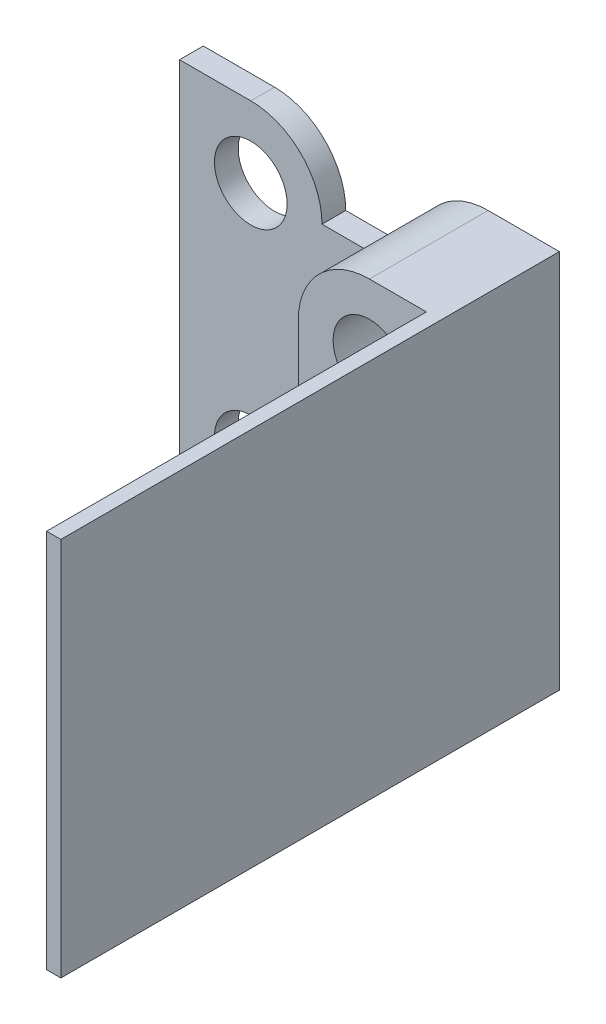
SolidWorks part; units mm, degrees
ref_plane "Front Plane" through (0, 0, 0) normal (0, 0, 1) x (1, 0, 0)
ref_plane "Top Plane" through (0, 0, 0) normal (0, 1, 0) x (1, 0, 0)
ref_plane "Right Plane" through (0, 0, 0) normal (1, 0, 0) x (0, 0, -1)
sketch "Sketch1" plane through (0, 0, 0) normal (0, 0, 1) x (1, 0, 0)
  line L0 (45, 50) -> (0, 50) construction
  line L1 (0, 50) -> (0, 0) construction
  line L2 (-15, 65) -> (0, 65)
  line L3 (60, 65) -> (60, 41.9663)
  line L4 (15, 50) -> (30, 50)
  line L5 (12.6521, -15) -> (-15, -15)
  line L6 (-15, -15) -> (-15, 65)
  line L7 (60, 41.9663) -> (60, -15)
  line L8 (60, -15) -> (12.6521, -15)
  line L9 (45, 65) -> (60, 65)
  circle A0 centre (0, 0) radius 7.65
  circle A1 centre (45, 50) radius 7.65
  circle A2 centre (0, 50) radius 7.65
  arc A3 (45, 65) -> (30, 50) centre (45, 50) ccw
  arc A4 (0, 65) -> (15, 50) centre (0, 50) cw
  dimension "D1" = 15.3
  dimension "D4" = 15
  dimension "D5" = 15
  dimension "D2" = 45
  dimension "D3" = 50
  dimension "D6" = 15
  dimension "D7" = 15
extrude "Boss-Extrude2" add sketch "Sketch1" along normal blind 5
sketch "Sketch2" plane through (0, 0, 5) normal (0, 0, 1) x (1, 0, 0)
  line L0 (-15, -15) -> (60, -15) construction
  line L1 (60, 65) -> (57, 65)
  line L2 (60, 65) -> (60, -15)
  line L3 (60, -15) -> (57, -15)
  line L4 (57, 65) -> (57, -15)
  dimension "D1" = 3
extrude "Boss-Extrude3" add sketch "Sketch2" along normal blind 100
sketch "Sketch3" plane through (0, 0, 5) normal (0, 0, 1) x (1, 0, 0)
  line L0 (30, 50) -> (30, 35)
  line L1 (30, 35) -> (57, 35)
  line L2 (57, 65) -> (57, -15) construction
  line L3 (57, 35) -> (57, 65)
  line L4 (57, 65) -> (45, 65)
  circle A0 centre (45, 50) radius 7.65
  arc A1 (45, 65) -> (30, 50) centre (45, 50) ccw
extrude "Boss-Extrude4" add sketch "Sketch3" along normal blind 20
